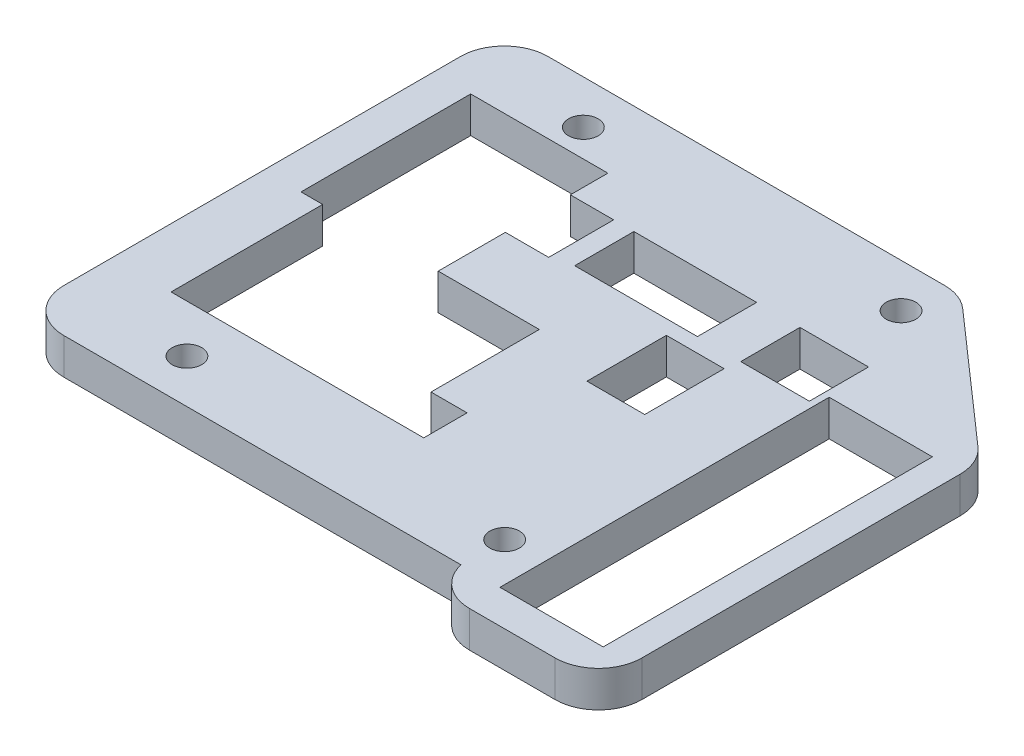
SolidWorks part; units mm, degrees
ref_plane "前视基准面" through (0, 0, 0) normal (0, 0, 1) x (1, 0, 0)
ref_plane "上视基准面" through (0, 0, 0) normal (0, 1, 0) x (1, 0, 0)
ref_plane "右视基准面" through (0, 0, 0) normal (1, 0, 0) x (0, 0, -1)
sketch "草图1" plane through (0, 0, 0) normal (0, 1, 0) x (1, 0, 0)
  line L0 (6, 0.3) -> (143.8, 0.3)
  line L1 (6, 0) -> (143.8, 0) construction
  line L2 (0, -6) -> (0, -68.8) construction
  line L3 (6, -74.8) -> (143.8, -74.8) construction
  line L4 (149.8, -6) -> (149.8, -68.8) construction
  line L5 (150.1, -6) -> (150.1, -68.8)
  line L6 (6, -75.1) -> (143.8, -75.1)
  line L7 (-0.3, -6) -> (-0.3, -68.8)
  arc A0 (143.8, 0) -> (149.8, -6) centre (143.8, -6) cw construction
  arc A1 (143.8, -74.8) -> (149.8, -68.8) centre (143.8, -68.8) ccw construction
  arc A2 (0, -68.8) -> (6, -74.8) centre (6, -68.8) ccw construction
  arc A3 (6, 0) -> (0, -6) centre (6, -6) ccw construction
  arc A4 (143.8, 0.3) -> (150.1, -6) centre (143.8, -6) cw
  arc A5 (143.8, -75.1) -> (150.1, -68.8) centre (143.8, -68.8) ccw
  arc A6 (-0.3, -68.8) -> (6, -75.1) centre (6, -68.8) ccw
  arc A7 (6, 0.3) -> (-0.3, -6) centre (6, -6) ccw
  point P7 (149.8, 0)
  point P12 (0, -74.8)
  point P15 (0, 0)
  dimension "D3" = 6
  dimension "D1" = 74.8
  dimension "D2" = 149.8
  dimension "D4" = 0.3
sketch "草图2" plane through (0, 0, 0) normal (0, -1, 0) x (-1, 0, 0)
  line L0 (-122.6, -55.35) -> (-108.9, -55.35) construction
  line L1 (-122.6, -69.85) -> (-108.9, -69.85) construction
  line L2 (-122.6, -69.85) -> (-122.6, -63.95) construction
  line L3 (-122.6, -63.95) -> (-108.9, -63.95) construction
  line L4 (-108.9, -69.85) -> (-108.9, -63.95) construction
  line L5 (-135.3, -1.25) -> (-35.3, -1.25) construction
  line L6 (-135.3, -1.25) -> (-135.3, -73.55) construction
  line L7 (-135.3, -73.55) -> (-35.3, -73.55) construction
  line L8 (-35.3, -1.25) -> (-35.3, -73.55) construction
  line L9 (-108.9, -61.25) -> (-108.9, -55.35) construction
  line L10 (-122.6, -61.25) -> (-108.9, -61.25) construction
  line L11 (-122.6, -61.25) -> (-122.6, -55.35) construction
  line L12 (-122.6, -46.75) -> (-108.9, -46.75) construction
  line L13 (-108.9, -52.65) -> (-108.9, -46.75) construction
  line L14 (-122.6, -52.65) -> (-108.9, -52.65) construction
  line L15 (-122.6, -52.65) -> (-122.6, -46.75) construction
  line L16 (-122.6, -38.15) -> (-108.9, -38.15) construction
  line L17 (-108.9, -44.05) -> (-108.9, -38.15) construction
  line L18 (-122.6, -44.05) -> (-108.9, -44.05) construction
  line L19 (-122.6, -44.05) -> (-122.6, -38.15) construction
  line L20 (0, -6) -> (0, -68.8) construction
  line L21 (-35.3, -73.55) -> (-0.8, -73.55) construction
  line L22 (-120.25, -26.65) -> (-111.25, -26.65) construction
  line L23 (-120.25, -26.65) -> (-120.25, -33.15) construction
  line L24 (-120.25, -33.15) -> (-111.25, -33.15) construction
  line L25 (-111.25, -26.65) -> (-111.25, -33.15) construction
  line L26 (-85.8, -48.75) -> (-81.1, -48.75) construction
  line L27 (-85.8, -48.75) -> (-85.8, -58.15) construction
  line L28 (-85.8, -58.15) -> (-81.1, -58.15) construction
  line L29 (-81.1, -48.75) -> (-81.1, -58.15) construction
  line L30 (-71.5, -48.65) -> (-68.2, -48.65) construction
  line L31 (-71.5, -48.65) -> (-71.5, -57.55) construction
  line L32 (-71.5, -57.55) -> (-68.2, -57.55) construction
  line L33 (-68.2, -48.65) -> (-68.2, -57.55) construction
  line L34 (-43.1, -45.05) -> (-38.6, -45.05) construction
  line L35 (-43.1, -45.05) -> (-43.1, -59.05) construction
  line L36 (-43.1, -59.05) -> (-38.6, -59.05) construction
  line L37 (-38.6, -45.05) -> (-38.6, -59.05) construction
  line L38 (-45.3, -61.55) -> (-40.8, -61.55) construction
  line L39 (-45.3, -61.55) -> (-45.3, -66.05) construction
  line L40 (-45.3, -66.05) -> (-40.8, -66.05) construction
  line L41 (-40.8, -61.55) -> (-40.8, -66.05) construction
  line L42 (-0.8, -73.55) -> (-0.8, -1.25) construction
  line L43 (-0.8, -1.25) -> (-35.3, -1.25) construction
  line L44 (-149.8, -6) -> (-149.8, -68.8) construction
  line L45 (-30.8, -34.65) -> (-27.3, -34.65) construction
  line L46 (-30.8, -34.65) -> (-30.8, -40.15) construction
  line L47 (-30.8, -40.15) -> (-27.3, -40.15) construction
  line L48 (-27.3, -34.65) -> (-27.3, -40.15) construction
  line L49 (-120.75, -33.65) -> (-110.75, -33.65)
  line L50 (-110.75, -26.15) -> (-110.75, -33.65)
  line L51 (-120.75, -26.15) -> (-110.75, -26.15)
  line L52 (-120.75, -26.15) -> (-120.75, -33.65)
  line L53 (-86.3, -48.25) -> (-86.3, -58.65)
  line L54 (-86.3, -58.65) -> (-80.6, -58.65)
  line L55 (-80.6, -48.25) -> (-80.6, -58.65)
  line L56 (-86.3, -48.25) -> (-80.6, -48.25)
  line L57 (-72, -48.15) -> (-72, -58.05)
  line L58 (-72, -58.05) -> (-67.7, -58.05)
  line L59 (-67.7, -48.15) -> (-67.7, -58.05)
  line L60 (-72, -48.15) -> (-67.7, -48.15)
  line L61 (-31.3, -34.15) -> (-31.3, -40.65)
  line L62 (-31.3, -40.65) -> (-26.8, -40.65)
  line L63 (-26.8, -34.15) -> (-26.8, -40.65)
  line L64 (-31.3, -34.15) -> (-26.8, -34.15)
  line L65 (-43.6, -44.55) -> (-43.6, -59.55)
  line L66 (-43.6, -59.55) -> (-38.1, -59.55)
  line L67 (-38.1, -44.55) -> (-38.1, -59.55)
  line L68 (-43.6, -44.55) -> (-38.1, -44.55)
  line L69 (-45.8, -61.05) -> (-45.8, -66.55)
  line L70 (-45.8, -66.55) -> (-40.3, -66.55)
  line L71 (-40.3, -61.05) -> (-40.3, -66.55)
  line L72 (-45.8, -61.05) -> (-40.3, -61.05)
  line L73 (-122.9, -44.35) -> (-108.6, -44.35)
  line L74 (-108.6, -44.35) -> (-108.6, -37.85)
  line L75 (-122.9, -37.85) -> (-108.6, -37.85)
  line L76 (-122.9, -44.35) -> (-122.9, -37.85)
  line L77 (-122.9, -52.95) -> (-108.6, -52.95)
  line L78 (-108.6, -52.95) -> (-108.6, -46.45)
  line L79 (-122.9, -46.45) -> (-108.6, -46.45)
  line L80 (-122.9, -52.95) -> (-122.9, -46.45)
  line L81 (-122.9, -61.55) -> (-108.6, -61.55)
  line L82 (-108.6, -61.55) -> (-108.6, -55.05)
  line L83 (-122.9, -55.05) -> (-108.6, -55.05)
  line L84 (-122.9, -61.55) -> (-122.9, -55.05)
  line L85 (-122.9, -70.15) -> (-108.6, -70.15)
  line L86 (-108.6, -70.15) -> (-108.6, -63.65)
  line L87 (-122.9, -63.65) -> (-108.6, -63.65)
  line L88 (-122.9, -70.15) -> (-122.9, -63.65)
  circle A0 centre (-103.2, -9.35) radius 1.65 construction
  circle A1 centre (-103.2, -64.25) radius 1.65 construction
  circle A2 centre (-59.2, -64.25) radius 1.65 construction
  circle A3 centre (-59.2, -9.35) radius 1.65 construction
  circle A4 centre (-130.8, -5.6) radius 1.25 construction
  circle A5 centre (-131.1, -55.65) radius 1.25 construction
  circle A6 centre (-47.7, -4.85) radius 1.25 construction
  circle A7 centre (-48.1, -68.75) radius 1.25 construction
  circle A8 centre (-22.8, -70.3) radius 1.25 construction
  circle A9 centre (-5.05, -71.05) radius 1.25 construction
  circle A10 centre (-5.05, -3.25) radius 1.25 construction
  circle A11 centre (-19, -37.4) radius 3.6 construction
  circle A12 centre (-103.2, -9.35) radius 2.05
  circle A13 centre (-59.2, -9.35) radius 2.05
  circle A14 centre (-59.2, -64.25) radius 2.05
  circle A15 centre (-103.2, -64.25) radius 2.05
  circle A16 centre (-19, -37.4) radius 4.1
  circle A17 centre (-130.8, -5.6) radius 1.75
  circle A18 centre (-131.1, -55.65) radius 1.75
  circle A19 centre (-48.1, -68.75) radius 1.75
  circle A20 centre (-22.8, -70.3) radius 1.75
  circle A21 centre (-5.05, -71.05) radius 1.75
  circle A22 centre (-5.05, -3.25) radius 1.75
  circle A23 centre (-47.7, -4.85) radius 1.75
  point P22 (0, -37.4)
  point P23 (-135.3, -37.4)
  point P28 (-115.75, -33.15)
  point P29 (-115.75, -38.15)
  point P30 (-111.25, -29.9)
  point P31 (-108.9, -41.1)
  point P79 (-0.8, -37.4)
  point P81 (-27.3, -37.4)
  dimension "D21" = 3.3
  dimension "D34" = 2.5
  dimension "D53" = 7.2
  dimension "D1" = 13.7
  dimension "D2" = 5.9
  dimension "D3" = 72.3
  dimension "D4" = 3.7
  dimension "D5" = 12.7
  dimension "D7" = 14.5
  dimension "D8" = 100
  dimension "D9" = 2.7
  dimension "D10" = 9
  dimension "D11" = 6.5
  dimension "D12" = 11.2
  dimension "D13" = 15.4
  dimension "D14" = 9.4
  dimension "D15" = 4.7
  dimension "D16" = 23.1
  dimension "D17" = 3.3
  dimension "D18" = 8.9
  dimension "D19" = 16
  dimension "D20" = 37.4
  dimension "D22" = 8.1
  dimension "D23" = 32.1
  dimension "D24" = 44
  dimension "D25" = 9.3
  dimension "D26" = 14
  dimension "D27" = 4.5
  dimension "D28" = 4.5
  dimension "D29" = 4.5
  dimension "D30" = 3.3
  dimension "D31" = 5.5
  dimension "D32" = 7.5
  dimension "D33" = 14.5
  dimension "D35" = 34.5
  dimension "D36" = 2
  dimension "D37" = 4.25
  dimension "D38" = 2.5
  dimension "D39" = 3.25
  dimension "D40" = 22
  dimension "D41" = 4.8
  dimension "D42" = 12.8
  dimension "D43" = 3.6
  dimension "D44" = 12.4
  dimension "D45" = 4.35
  dimension "D46" = 4.5
  dimension "D47" = 4.2
  dimension "D48" = 17.9
  dimension "D49" = 18.2
  dimension "D50" = 3.5
  dimension "D51" = 5.5
  dimension "D52" = 8.3
  dimension "D54" = 0.4
  dimension "D55" = 0.5
  dimension "D56" = 0.5
  dimension "D57" = 0.5
  dimension "D58" = 0.3
  dimension "D6" = 4
sketch "草图3" plane through (0, 0, 0) normal (0, 1, 0) x (1, 0, 0)
  line L0 (135.3, -1.25) -> (135.3, -73.55) construction
  line L1 (143.8, 0) -> (135.3, 0)
  line L2 (149.8, -6) -> (149.8, -68.8)
  line L3 (143.8, -74.8) -> (135.3, -74.8)
  line L4 (135.3, 0) -> (135.3, -74.8)
  line L5 (6, -74.8) -> (143.8, -74.8) construction
  arc A0 (143.8, 0) -> (149.8, -6) centre (143.8, -6) cw
  arc A1 (149.8, -68.8) -> (143.8, -74.8) centre (143.8, -68.8) cw
  point P17 (149.8, 0)
  dimension "D1" = 6
sketch "草图4" plane through (0, 0, 0) normal (0, 1, 0) x (1, 0, 0)
  line L0 (122.9, -62.85) -> (108.6, -62.85)
  line L1 (122.6, -63.15) -> (108.9, -63.15) construction
  line L2 (122.6, -63.15) -> (122.6, -70.65) construction
  line L3 (122.6, -70.65) -> (108.9, -70.65) construction
  line L4 (108.9, -63.15) -> (108.9, -70.65) construction
  line L5 (122.6, -69.85) -> (122.6, -63.95) construction
  line L6 (108.6, -62.85) -> (108.6, -70.95)
  line L7 (108.9, -69.85) -> (108.9, -63.95) construction
  line L8 (122.6, -54.55) -> (108.9, -54.55) construction
  line L9 (108.9, -54.55) -> (108.9, -62.05) construction
  line L10 (122.6, -62.05) -> (108.9, -62.05) construction
  line L11 (122.6, -54.55) -> (122.6, -62.05) construction
  line L12 (122.6, -45.95) -> (108.9, -45.95) construction
  line L13 (108.9, -45.95) -> (108.9, -53.45) construction
  line L14 (122.6, -53.45) -> (108.9, -53.45) construction
  line L15 (122.6, -45.95) -> (122.6, -53.45) construction
  line L16 (122.6, -37.35) -> (108.9, -37.35) construction
  line L17 (108.9, -37.35) -> (108.9, -44.85) construction
  line L18 (122.6, -44.85) -> (108.9, -44.85) construction
  line L19 (122.6, -37.35) -> (122.6, -44.85) construction
  line L20 (122.9, -70.95) -> (108.6, -70.95)
  line L21 (122.9, -62.85) -> (122.9, -70.95)
  line L22 (122.9, -54.25) -> (108.6, -54.25)
  line L23 (108.6, -54.25) -> (108.6, -62.35)
  line L24 (122.9, -62.35) -> (108.6, -62.35)
  line L25 (122.9, -54.25) -> (122.9, -62.35)
  line L26 (122.9, -45.65) -> (108.6, -45.65)
  line L27 (108.6, -45.65) -> (108.6, -53.75)
  line L28 (122.9, -53.75) -> (108.6, -53.75)
  line L29 (122.9, -45.65) -> (122.9, -53.75)
  line L30 (122.9, -37.05) -> (108.6, -37.05)
  line L31 (108.6, -37.05) -> (108.6, -45.15)
  line L32 (122.9, -45.15) -> (108.6, -45.15)
  line L33 (122.9, -37.05) -> (122.9, -45.15)
  point P11 (108.9, -66.9)
  point P12 (108.9, -66.9)
  dimension "D1" = 7.5
  dimension "D3" = 1.1
  dimension "D4" = 0.3
  dimension "D2" = 4
extrude "拉伸-薄壁1" add sketch "草图2" along normal blind 5 thin contours A13 | A12 | A14 | A15
sketch "草图6" plane through (0, 0, 0) normal (0, 1, 0) x (1, 0, 0)
  line L0 (107.1972, -4.8085) -> (124.8642, -20.3581)
  line L1 (126.9, -24.8621) -> (126.9, -68.95)
  line L2 (120.9, -74.95) -> (109.0462, -74.95)
  line L4 (59.2, -3.3) -> (103.2, -3.3)
  line L6 (59.2, -3.3) -> (48.25, -3.3)
  line L8 (122.9, -37.05) -> (122.9, -45.15) construction
  line L9 (120.75, -26.15) -> (110.75, -26.15) construction
  line L10 (122.9, -70.95) -> (108.6, -70.95) construction
  line L11 (108.6, -62.85) -> (108.6, -70.95) construction
  line L12 (42.2, -9.35) -> (42.2, -64.3)
  line L13 (103.2, -70.3) -> (48.2, -70.3)
  circle A0 centre (103.2, -9.35) radius 6.05 construction
  circle A1 centre (103.2, -64.25) radius 6.05 construction
  arc A2 (107.1972, -4.8085) -> (103.2, -3.3) centre (103.2, -9.35) ccw
  arc A4 (109.0462, -74.95) -> (103.2, -70.3) centre (109.0462, -68.95) cw
  circle A5 centre (59.2, -64.25) radius 6.05 construction
  arc A6 (126.9, -68.95) -> (120.9, -74.95) centre (120.9, -68.95) cw
  arc A7 (124.8642, -20.3581) -> (126.9, -24.8621) centre (120.9, -24.8621) cw
  circle A8 centre (59.2, -9.35) radius 6.05 construction
  arc A9 (42.2, -64.3) -> (48.2, -70.3) centre (48.2, -64.3) ccw
  circle A10 centre (103.2, -9.35) radius 2.05 construction
  circle A11 centre (103.2, -64.25) radius 2.05 construction
  circle A12 centre (59.2, -64.25) radius 2.05 construction
  circle A13 centre (103.2, -9.35) radius 2.05
  circle A14 centre (103.2, -64.25) radius 2.05
  circle A15 centre (59.2, -64.25) radius 2.05
  circle A16 centre (59.2, -9.35) radius 2.05 construction
  circle A17 centre (59.2, -9.35) radius 2.05
  arc A18 (48.25, -3.3) -> (42.2, -9.35) centre (48.25, -9.35) ccw
  point P37 (105.6, -74.95)
  point P42 (126.9, -22.15)
  dimension "D6" = 6
  dimension "D7" = 12.1
  dimension "D8" = 6
  dimension "D9" = 6
  dimension "D10" = 6
  dimension "D11" = 6
  dimension "D1" = 4
  dimension "D2" = 4
  dimension "D3" = 4
  dimension "D4" = 3
  dimension "D5" = 17
extrude "凸台-拉伸1" add sketch "草图6" against normal up to surface (5 mm away) up to face at (97.15, -5, 9.35)
sketch "草图7" plane through (0, -5, 3) normal (0, -1, 0) x (1, 0, 0)
  line L9 (80.466, 15.85) -> (96.6871, 15.85) construction
  line L43 (107.2, -14.628) -> (107.2, -27.7853) construction
  line L44 (108.9, 22) -> (108.9, 67) construction
  line L45 (122.6, 67) -> (108.9, 67) construction
  line L46 (122.6, 22) -> (122.6, 67) construction
  line L47 (122.6, 22) -> (108.9, 22) construction
  line L48 (120.2, 9.55) -> (113.2, 9.55)
  line L49 (120.2, 4.55) -> (120.2, 9.55)
  line L50 (113.2, 4.55) -> (120.2, 4.55)
  line L51 (113.2, 9.55) -> (113.2, 4.55)
  line L52 (80.4, 48.65) -> (80.4, 33.65)
  line L53 (85.4, 48.65) -> (80.4, 48.65)
  line L54 (97.9, 36.55) -> (89.9, 36.55)
  line L55 (97.9, 25.55) -> (97.9, 36.55)
  line L56 (89.9, 25.55) -> (97.9, 25.55)
  line L57 (89.9, 36.55) -> (89.9, 25.55)
  line L58 (66.4, 33.65) -> (80.4, 33.65)
  line L59 (50.4, 54.65) -> (50.4, 33.65)
  line L60 (85.4, 54.65) -> (50.4, 54.65)
  line L61 (85.4, 48.65) -> (85.4, 54.65)
  line L62 (47.4, 10.15) -> (66.4, 10.15)
  line L63 (47.4, 33.65) -> (47.4, 10.15)
  line L64 (50.4, 33.65) -> (47.4, 33.65)
  line L65 (66.4, 10.15) -> (66.4, 15.35)
  line L66 (66.4, 24.35) -> (72.4, 24.35)
  line L67 (66.4, 24.35) -> (66.4, 33.65)
  line L68 (72.4, 15.35) -> (66.4, 15.35)
  line L69 (122.9, 21.7) -> (122.9, 67.3)
  line L70 (122.9, 67.3) -> (108.6, 67.3)
  line L71 (72.4, 24.35) -> (72.4, 15.35)
  line L72 (92.2, 15.35) -> (75.2, 15.35)
  line L73 (92.2, 23.55) -> (92.2, 15.35)
  line L74 (75.2, 23.55) -> (92.2, 23.55)
  line L75 (107.7, 23.55) -> (107.7, 15.35)
  line L76 (98.2, 23.55) -> (107.7, 23.55)
  line L77 (98.2, 15.35) -> (98.2, 23.55)
  line L78 (107.7, 15.35) -> (98.2, 15.35)
  line L79 (75.2, 15.35) -> (75.2, 23.55)
  line L80 (108.6, 21.7) -> (108.6, 67.3)
  line L81 (122.9, 21.7) -> (108.6, 21.7)
  circle A0 centre (103.2, 61.25) radius 2.05 construction
  circle A1 centre (103.2, 61.25) radius 2.05
  circle A5 centre (59.2, 61.25) radius 2.05
  circle A6 centre (103.2, 61.25) radius 2.05
extrude "切除-拉伸1" cut sketch "草图7" against normal blind 5 contours L81 L69 L70 L80 | L78 L75 L76 L77 | L54 L57 L56 L55 | L79 L72 L73 L74 | L71 L66 L67 L58 L52 L53 L61 L60 L59 L64 L63 L62 L65 L68
equation "\"D1@草图3\"=\"D3@草图1\""
